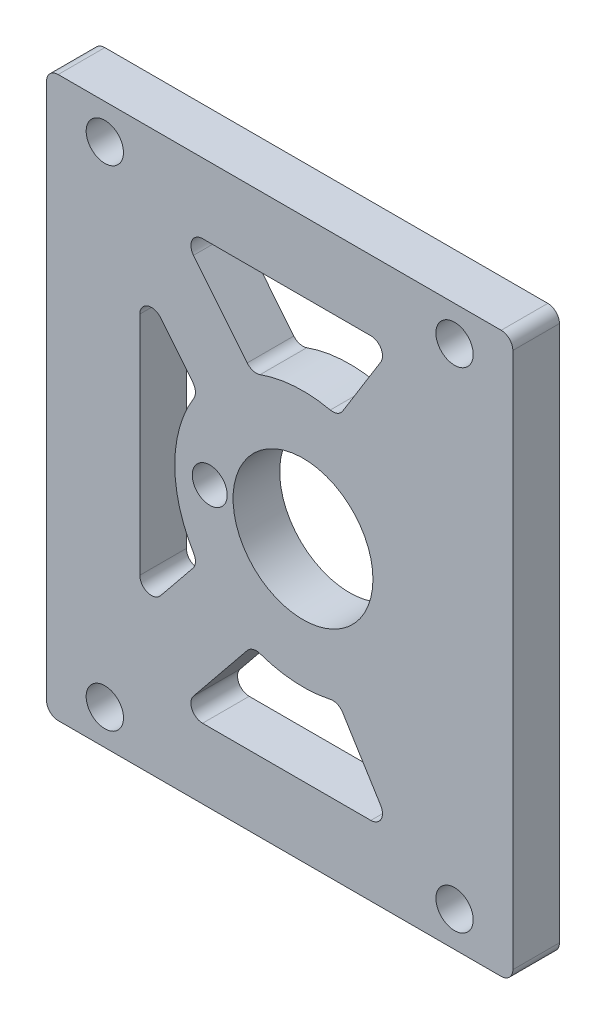
SolidWorks part; units mm, degrees
ref_plane "正面" through (0, 0, 0) normal (0, 0, 1) x (1, 0, 0)
ref_plane "平面" through (0, 0, 0) normal (0, 1, 0) x (1, 0, 0)
ref_plane "右側面" through (0, 0, 0) normal (1, 0, 0) x (0, 0, -1)
sketch "ｽｹｯﾁ1" plane through (0, 0, 0) normal (0, 0, 1) x (1, 0, 0)
  line L1 (0, 0) -> (40, 0)
  line L2 (0, 0) -> (0, 48)
  line L3 (0, 48) -> (40, 48)
  line L4 (40, 0) -> (40, 48)
  circle A0 centre (5, 45) radius 1.6
  circle A1 centre (5, 3) radius 1.6
  circle A2 centre (35, 45) radius 1.6
  circle A3 centre (35, 3) radius 1.6
  circle A6 centre (22, 24) radius 6
  point P17 (40, 24)
  dimension "D1" = 3
  dimension "D2" = 5
  dimension "D3" = 3
  dimension "D4" = 5
  dimension "D6" = 3
  dimension "D7" = 5
  dimension "D8" = 3
  dimension "D9" = 3.2
  dimension "D10" = 3.2
  dimension "D11" = 3.2
  dimension "D12" = 3.2
  dimension "D15" = 22
  dimension "D18" = 0
  dimension "D19" = 12
  dimension "D5" = 5
  dimension "D13" = 48
  dimension "D14" = 40
extrude "ﾎﾞｽ - 押し出し1" add sketch "ｽｹｯﾁ1" along normal blind 4
sketch "ｽｹｯﾁ3" plane through (0, 0, 4) normal (0, 0, 1) x (1, 0, 0)
  circle A0 centre (14, 24) radius 1.5
  circle A1 centre (22, 24) radius 6 construction
  dimension "D1" = 0
  dimension "D2" = 3
  dimension "D3" = 8
extrude "ｶｯﾄ - 押し出し1" cut sketch "ｽｹｯﾁ3" against normal through all
sketch "ｽｹｯﾁ4" plane through (0, 0, 0) normal (0, 0, -1) x (-1, 0, 0)
  line L0 (-22, 24) -> (-35, 45) construction
  line L5 (-35, 45) -> (-5, 45) construction
  line L6 (-5, 45) -> (-22, 24) construction
  line L7 (-22, 24) -> (-35, 3) construction
  line L8 (-35, 3) -> (-5, 3) construction
  line L9 (-5, 3) -> (-22, 24) construction
  line L10 (-25.0196, 13.4226) -> (-29.6145, 6)
  line L11 (-29.6145, 6) -> (-11.2884, 6)
  line L12 (-11.2884, 6) -> (-17.6729, 13.8868)
  line L13 (-25.0196, 34.5774) -> (-29.6145, 42)
  line L14 (-29.6145, 42) -> (-11.2884, 42)
  line L15 (-11.2884, 42) -> (-17.6729, 34.1132)
  line L16 (-13.0095, 30.338) -> (-8, 36.5261)
  line L17 (-8, 36.5261) -> (-8, 11.4739)
  line L18 (-8, 11.4739) -> (-13.0095, 17.662)
  line L19 (0, 48) -> (0, 0) construction
  circle A0 centre (-22, 24) radius 11
  circle A1 centre (-22, 24) radius 6 construction
  dimension "D10" = 5
  dimension "D1" = 3
  dimension "D2" = 3
  dimension "D3" = 3
  dimension "D4" = 3
  dimension "D5" = 3
  dimension "D6" = 3
  dimension "D7" = 3
  dimension "D8" = 8
  dimension "D9" = 3
extrude "ｶｯﾄ - 押し出し2" cut sketch "ｽｹｯﾁ4" against normal blind 10 contours A0 L15 L14 L13 | A0 L18 L17 L16 | A0 L10 L11 L12
fillet "ﾌｨﾚｯﾄ1" radius 1 16 edges at (40, 48, 2) (0, 48, 2) (0, 0, 2) (40, 0, 2) (29.6145, 6, 2) (11.2884, 6, 2) (25.0196, 13.4226, 2) (17.6729, 13.8868, 2) (29.6145, 42, 2) (25.0196, 34.5774, 2) (17.6729, 34.1132, 2) (11.2884, 42, 2) (8, 36.5261, 2) (8, 11.4739, 2) (13.0095, 17.662, 2) (13.0095, 30.338, 2)
